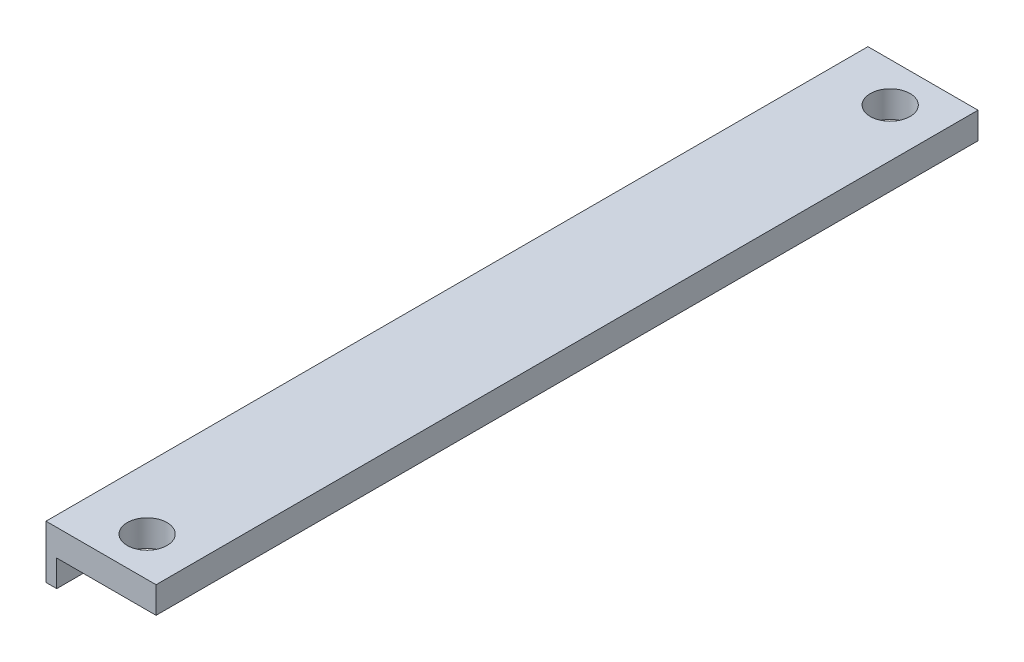
SolidWorks part; units mm, degrees
ref_plane "Front Plane" through (0, 0, 0) normal (0, 0, 1) x (1, 0, 0)
ref_plane "Top Plane" through (0, 0, 0) normal (0, 1, 0) x (1, 0, 0)
ref_plane "Right Plane" through (0, 0, 0) normal (1, 0, 0) x (0, 0, -1)
sketch "Sketch1" plane through (0, 0, 0) normal (0, 1, 0) x (1, 0, 0)
  line L1 (-54.762, 30.9684) -> (54, 30.9684)
  line L2 (-54.762, 30.9684) -> (-54.762, -30.9684)
  line L3 (-54.762, -30.9684) -> (54, -30.9684)
  line L4 (54, 30.9684) -> (54, -30.9684)
  point P0 (0, 0)
extrude "Boss-Extrude1" add sketch "Sketch1" along normal blind 2
sketch "Sketch2" plane through (0, 2, 0) normal (0, 1, 0) x (1, 0, 0)
  line L0 (-54.762, 30.9684) -> (-50.9216, 27.9966)
  line L1 (-54.762, 30.9684) -> (-54.762, -30.9684) construction
  line L3 (-54.762, 0) -> (54, 0) construction
  line L4 (54, -30.9684) -> (54, 30.9684) construction
  line L5 (-0.381, 30.9684) -> (-0.381, -30.9684) construction
  line L6 (54, 30.9684) -> (-54.762, 30.9684) construction
  line L7 (-54.762, -30.9684) -> (54, -30.9684) construction
  circle A0 centre (-50.9216, 27.9966) radius 1.5
ref_plane "Plane1" through (0, 0, 0) normal (0, 0, 1) x (1, 0, 0)
ref_plane "Plane2" through (-0.381, 0, 0) normal (-1, 0, 0) x (0, 0, 1)
extrude "Cut-Extrude1" cut sketch "Sketch2" against normal through all contours A0
mirror "Mirror1" about plane through (0, 0, 0) normal (0, 0, 1) of "Cut-Extrude1"
mirror "Mirror2" about plane through (-0.381, 0, 0) normal (-1, 0, 0) of "Mirror1", "Cut-Extrude1"
sketch "Sketch3" plane through (0, 2, 0) normal (0, 1, 0) x (1, 0, 0)
  line L1 (-47.0124, -28.2777) -> (47.0124, -28.2777)
  line L2 (-47.0124, -28.2777) -> (-47.0124, 28.2777)
  line L3 (-47.0124, 28.2777) -> (47.0124, 28.2777)
  line L4 (47.0124, -28.2777) -> (47.0124, 28.2777)
  line L5 (-47.0124, -28.2777) -> (47.0124, 28.2777) construction
  line L6 (-47.0124, 28.2777) -> (47.0124, -28.2777) construction
  point P0 (0, 0)
extrude "Cut-Extrude2" cut sketch "Sketch3" against normal through all
sketch "Sketch4" plane through (0, 2, 0) normal (0, 1, 0) x (1, 0, 0)
  line L0 (-34.0652, 0) -> (34.0652, 0) construction
  line L1 (-47.7447, -25.6583) -> (-52.7454, -25.6583)
  line L2 (-47.7447, -25.6583) -> (-47.7447, 25.6583)
  line L3 (-47.7447, 25.6583) -> (-52.7454, 25.6583)
  line L4 (-52.7454, -25.6583) -> (-52.7454, 25.6583)
  line L5 (-47.7447, -25.6583) -> (-52.7454, 25.6583) construction
  line L6 (-47.7447, 25.6583) -> (-52.7454, -25.6583) construction
  point P0 (-50.2451, 0)
extrude "Cut-Extrude3" [suppressed] cut sketch "Sketch4" against normal through all
sketch "Sketch5" plane through (0, 2, 0) normal (0, 1, 0) x (1, 0, 0)
  line L0 (-47.0648, 30.9684) -> (-47.0648, -30.9684)
  line L1 (54, 30.9684) -> (-54.762, 30.9684) construction
  line L2 (-54.762, -30.9684) -> (54, -30.9684) construction
  line L3 (-47.0648, -30.9684) -> (54, -30.9684)
  line L4 (54, -30.9684) -> (54, 30.9684)
  line L5 (54, 30.9684) -> (-47.0648, 30.9684)
extrude "Cut-Extrude4" [suppressed] cut sketch "Sketch5" against normal blind 10
sketch "Sketch6" plane through (0, 2, 0) normal (0, 1, 0) x (1, 0, 0)
  line L2 (-47.2763, 30.9684) -> (-47.2763, -30.9684)
  line L3 (-54.762, -30.9684) -> (54, -30.9684) construction
  line L4 (-47.2763, -30.9684) -> (54, -30.9684)
  line L5 (54, -30.9684) -> (54, 30.9684)
  line L6 (54, 30.9684) -> (-47.2763, 30.9684)
  point P0 (0, 0)
extrude "Cut-Extrude5" cut sketch "Sketch6" against normal blind 10
sketch "Sketch8" plane through (0, 2, 0) normal (0, 1, 0) x (1, 0, 0)
  line L0 (-54.762, 30.9684) -> (-55.5705, 30.9684)
  line L1 (-55.5705, 30.9684) -> (-55.5705, -30.9684)
  line L2 (-55.5705, -30.9684) -> (-54.762, -30.9684)
  line L3 (-54.762, -30.9684) -> (-54.762, 30.9684)
extrude "Boss-Extrude2" add sketch "Sketch8" against normal blind 4
